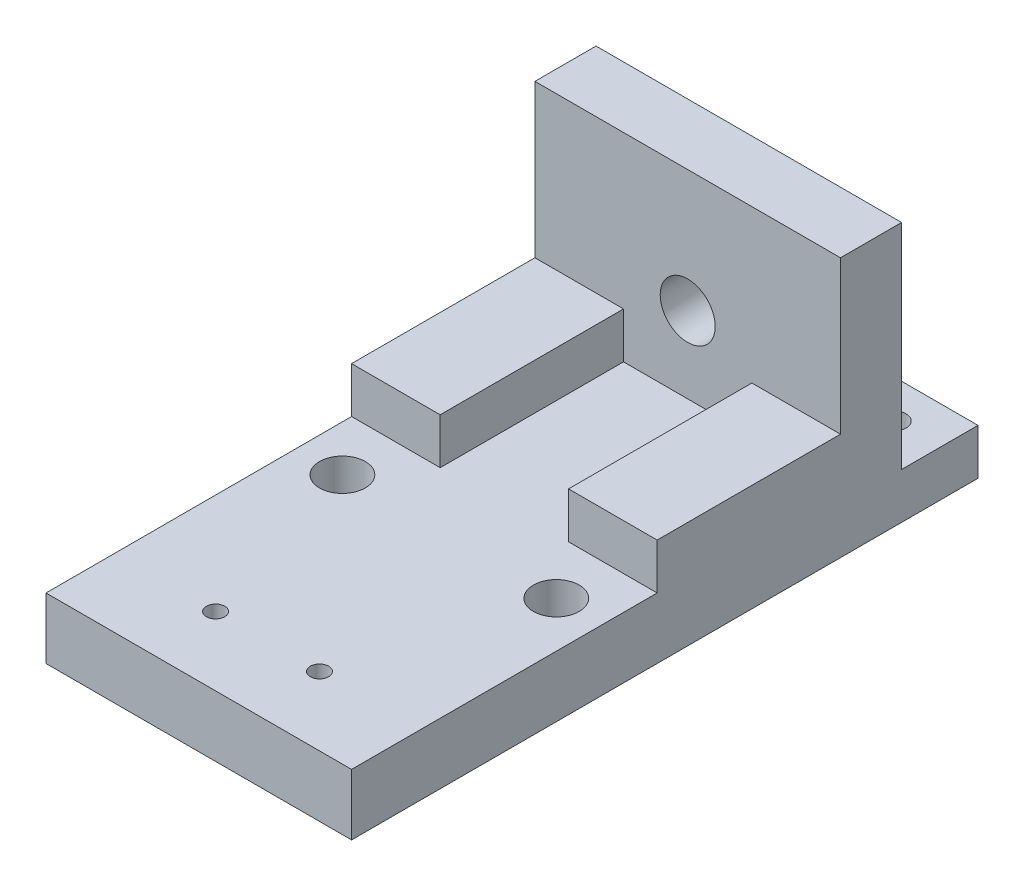
SolidWorks part; units mm, degrees
ref_plane "Ön Düzlem" through (0, 0, 0) normal (0, 0, 1) x (1, 0, 0)
ref_plane "Üst Düzlem" through (0, 0, 0) normal (0, 1, 0) x (1, 0, 0)
ref_plane "Sağ Düzlem" through (0, 0, 0) normal (1, 0, 0) x (0, 0, -1)
sketch "Çizim1" plane through (0, 0, 0) normal (1, 0, 0) x (0, 0, -1)
  line L0 (-127.6329, 26.7475) -> (-127.6329, 6.7475)
  line L1 (-127.6329, 6.7475) -> (77.3671, 6.7475)
  line L2 (77.3671, 6.7475) -> (77.3671, 21.7475)
  line L3 (77.3671, 21.7475) -> (52.3671, 21.7475)
  line L4 (52.3671, 21.7475) -> (52.3671, 91.7475)
  line L5 (52.3671, 91.7475) -> (32.3671, 91.7475)
  line L6 (32.3671, 91.7475) -> (32.3671, 41.7475)
  line L7 (32.3671, 41.7475) -> (-27.6329, 41.7475)
  line L8 (-27.6329, 41.7475) -> (-27.6329, 26.7475)
  line L9 (-27.6329, 26.7475) -> (-127.6329, 26.7475)
  dimension "D1" = 20
  dimension "D2" = 15
  dimension "D3" = 205
  dimension "D4" = 70
  dimension "D5" = 20
  dimension "D6" = 60
  dimension "D7" = 25
  dimension "D8" = 15
extrude "Yükseklik-Ekstrüzyon1" add sketch "Çizim1" along normal blind 100
sketch "Çizim2" plane through (0, 41.7475, 0) normal (0, 1, 0) x (1, 0, 0)
  line L0 (100, 32.3671) -> (0, 32.3671) construction
  line L1 (29, 32.3671) -> (71, 32.3671)
  line L2 (29, 32.3671) -> (29, -27.6329)
  line L3 (29, -27.6329) -> (71, -27.6329)
  line L4 (71, 32.3671) -> (71, -27.6329)
  line L5 (100, -27.6329) -> (0, -27.6329) construction
  dimension "D1" = 42
  dimension "D2" = 29
extrude "Kes-Ekstrüzyon1" cut sketch "Çizim2" against normal blind 15
sketch "Çizim3" plane through (0, 26.7475, 0) normal (0, 1, 0) x (1, 0, 0)
  line L0 (100, -127.6329) -> (0, -127.6329) construction
  line L1 (100, -27.6329) -> (100, -127.6329) construction
  line L2 (100, 77.3671) -> (0, 77.3671) construction
  line L3 (100, 77.3671) -> (100, 52.3671) construction
  circle A0 centre (15, 64.8671) radius 4
  circle A1 centre (85, 64.8671) radius 4
  circle A2 centre (33, -105.1329) radius 3
  circle A3 centre (67, -105.1329) radius 3
  dimension "D3" = 6
  dimension "D4" = 6
  dimension "D11" = 8
  dimension "D12" = 8
  dimension "D1" = 22.5
  dimension "D2" = 22.5
  dimension "D5" = 34
  dimension "D6" = 33
  dimension "D7" = 12.5
  dimension "D8" = 12.5
  dimension "D9" = 70
  dimension "D10" = 15
extrude "Kes-Ekstrüzyon2" cut sketch "Çizim3" against normal through all
sketch "Çizim4" plane through (0, 26.7475, 0) normal (0, 1, 0) x (1, 0, 0)
  line L0 (100, -27.6329) -> (100, -127.6329) construction
  line L1 (100, -127.6329) -> (0, -127.6329) construction
  circle A0 centre (15, -45.6329) radius 7.5
  circle A2 centre (85, -45.6329) radius 7.5
  point P2 (0, 0)
  dimension "D3" = 15
  dimension "D4" = 15
  dimension "D5" = 70
  dimension "D6" = 15
  dimension "D7" = 82
extrude "Kes-Ekstrüzyon5" cut sketch "Çizim4" against normal through all contours A2 | A0
sketch "Çizim5" plane through (0, 0, -52.3671) normal (0, 0, -1) x (-1, 0, 0)
  line L0 (-100, 21.7475) -> (-100, 91.7475) construction
  line L1 (-100, 6.7475) -> (0, 6.7475) construction
  circle A0 centre (-50, 51.7475) radius 9
  dimension "D3" = 18
  dimension "D1" = 50
  dimension "D2" = 45
extrude "Kes-Ekstrüzyon6" cut sketch "Çizim5" against normal through all
